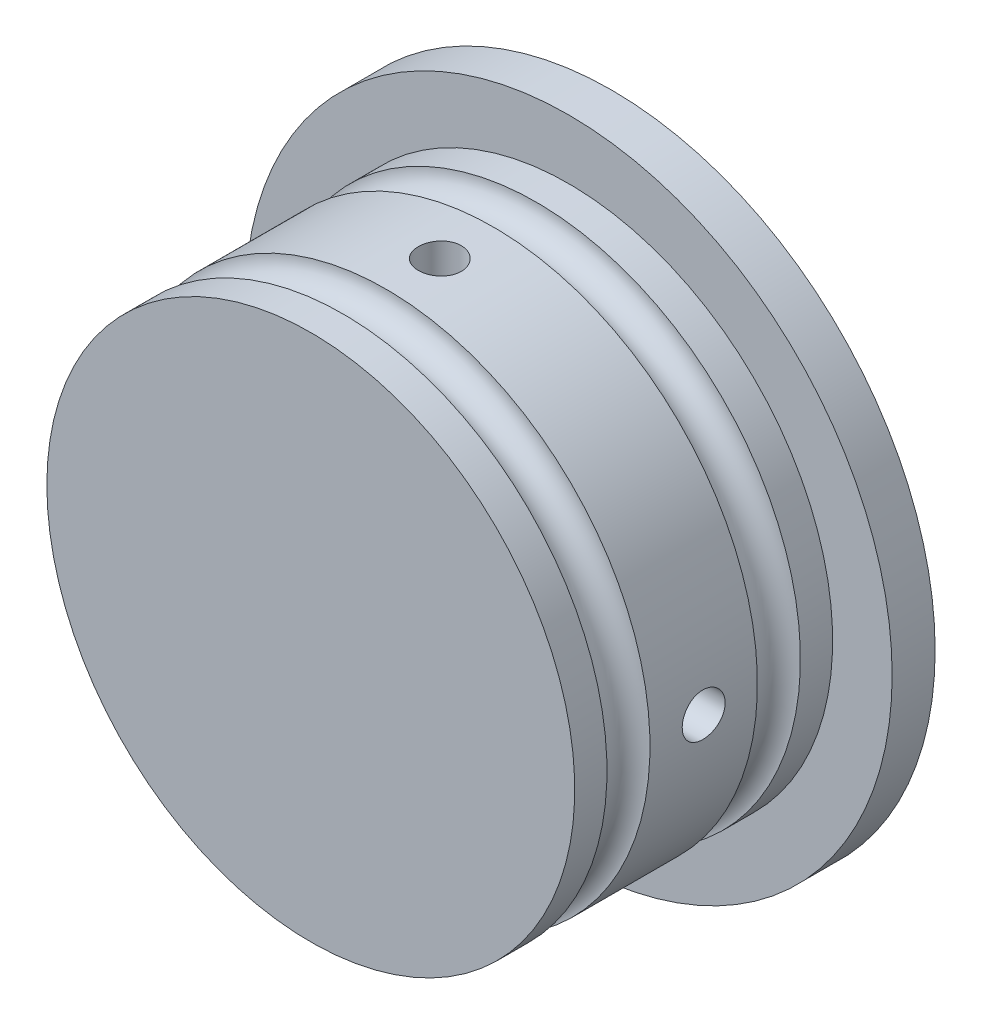
SolidWorks part; units mm, degrees
material "Stainless Steel (ferritic)"
ref_plane "Front Plane" through (0, 0, 0) normal (0, 0, 1) x (1, 0, 0)
ref_plane "Top Plane" through (0, 0, 0) normal (0, 1, 0) x (1, 0, 0)
ref_plane "Right Plane" through (0, 0, 0) normal (1, 0, 0) x (0, 0, -1)
sketch "Sketch1" plane through (0, 0, 0) normal (0, 1, 0) x (1, 0, 0)
  line L0 (0, 0) -> (0, 28)
  line L1 (0, 28) -> (45, 28)
  line L2 (45, 28) -> (45, 24)
  line L3 (45, 24) -> (24.5618, 24)
  line L4 (24.5618, 24) -> (24.5618, 21)
  line L6 (24.5618, 17) -> (24.5618, 7)
  line L8 (24.5618, 3) -> (24.5618, 0)
  line L9 (0, 0) -> (24.5618, 0)
  line L10 (0, 0) -> (0, -10) construction
  line L11 (30.099, 24) -> (30.099, 28)
  arc A0 (24.5618, 21) -> (24.5618, 17) centre (24.5618, 19) ccw
  arc A1 (24.5618, 7) -> (24.5618, 3) centre (24.5618, 5) ccw
  dimension "D1" = 24.5618
  dimension "D7" = 2
  dimension "D2" = 4
  dimension "D3" = 3
  dimension "D4" = 28
  dimension "D5" = 3
  dimension "D6" = 45
  dimension "D8" = 10
  dimension "D9" = 30.099
revolve "Revolve1" add sketch "Sketch1" angle 360 about L10
sketch "Sketch2" plane through (0, 0, -24) normal (0, 0, 1) x (1, 0, 0)
  circle A0 centre (0, 0) radius 37.5 construction
  point P0 (0, 37.5)
  point P2 (37.5, 0)
  point P4 (0, -37.5)
  point P6 (-37.5, 0)
  dimension "D1" = 75
hole_wizard "Ø4.0mm Dowel Hole1" positions "Sketch2" profile "Sketch3" hole size "Ø4.0" standard "ISO"
sketch "Sketch3" plane through (0, 37.5, -24) normal (1, 0, 0) x (0, -1, 0)
  line L0 (0, 0) -> (0, 4)
  line L1 (0, 4) -> (2, 4)
  line L2 (2, 4) -> (2, 0)
  line L5 (2, 0) -> (0, 0)
  line L11 (0, -6.35) -> (0, 107.95) construction
  dimension "Thru Hole Dia." = 4
  dimension "Thru Hole Depth" = 4
ref_plane "Plane1" through (0, 0, -17) normal (0, 0, 1) x (1, 0, 0)
ref_plane "Plane2" through (0, 0, -12) normal (0, 0, 1) x (1, 0, 0)
hole_wizard "Ø4.0mm Dowel Hole2" positions "3DSketch1" profile "Sketch5" hole size "Ø4.0" standard "ISO"
sketch3d "3DSketch1"
  line L0 (24.5618, 0, -12) -> (-24.5618, 0, -12)
  line L2 (0, -24.5618, -12) -> (0, 24.5618, -12)
  point P0 (0, 24.5618, -12)
  point P2 (24.5618, 0, -12)
  point P4 (0, -24.5618, -12)
  point P6 (-24.5618, 0, -12)
  dimension "D1" = 0
sketch "Sketch5" plane through (0, 24.5618, -12) normal (1, 0, 0) x (0, 0, 1)
  line L0 (0, 0) -> (0, 9.2017)
  line L1 (0, 9.2017) -> (2, 8)
  line L2 (2, 8) -> (2, 0)
  line L5 (2, 0) -> (0, 0)
  line L10 (0, 9.2017) -> (-2, 8) construction
  line L11 (0, -6.35) -> (0, 107.95) construction
  dimension "Hole Dia." = 4
  dimension "Hole Depth" = 8
  dimension "Drill Angle" = 118
hole_wizard "Ø6.0mm Dowel Hole1" positions "Sketch6" profile "Sketch7" hole size "Ø6.0" standard "ISO"
sketch "Sketch6" plane through (0, 0, -28) normal (0, 0, -1) x (-1, 0, 0)
  point P0 (0, 0)
sketch "Sketch7" plane through (0, 0, -28) normal (1, 0, 0) x (0, 1, 0)
  line L0 (0, 0) -> (0, 16.8026)
  line L1 (0, 16.8026) -> (3, 15)
  line L2 (3, 15) -> (3, 0)
  line L5 (3, 0) -> (0, 0)
  line L10 (0, 16.8026) -> (-3, 15) construction
  line L11 (0, -6.35) -> (0, 107.95) construction
  dimension "Hole Dia." = 6
  dimension "Hole Depth" = 15
  dimension "Drill Angle" = 118
